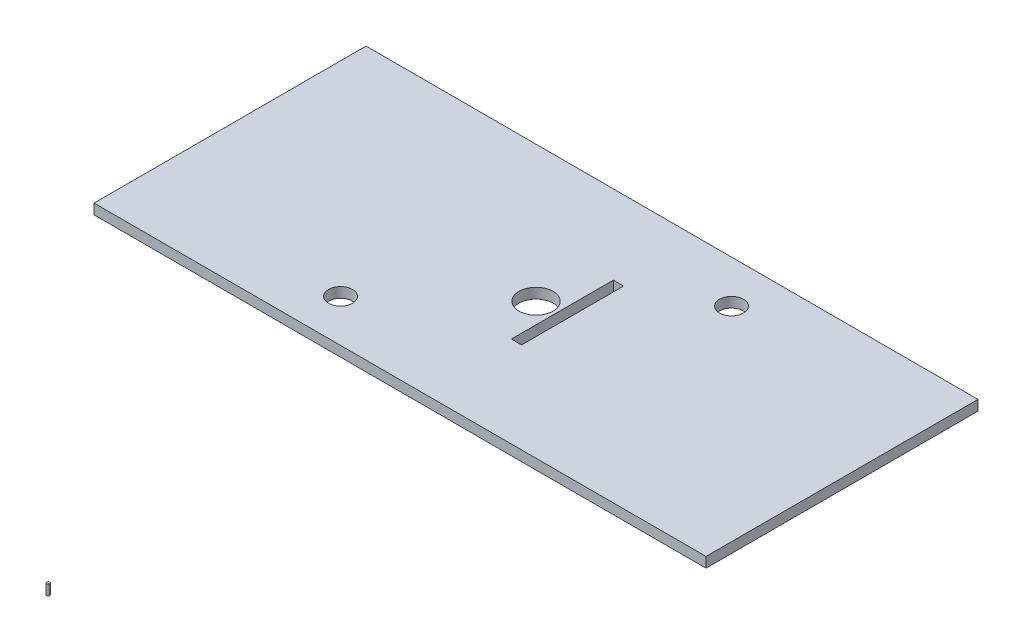
SolidWorks part; units mm, degrees
ref_plane "Plano frontal" through (0, 0, 0) normal (0, 0, 1) x (1, 0, 0)
ref_plane "Plano superior" through (0, 0, 0) normal (0, 1, 0) x (1, 0, 0)
ref_plane "Plano direito" through (0, 0, 0) normal (1, 0, 0) x (0, 0, -1)
sketch "Esboço1" plane through (0, 0, 0) normal (0, 1, 0) x (1, 0, 0)
  line L1 (90, -40) -> (-90, -40)
  line L2 (90, -40) -> (90, 40)
  line L3 (90, 40) -> (-90, 40)
  line L4 (-90, -40) -> (-90, 40)
  line L5 (90, -40) -> (-90, 40) construction
  line L6 (90, 40) -> (-90, -40) construction
  circle A0 centre (0, -143.5) radius 0.45
  circle A1 centre (0, 0) radius 5.025
  point P0 (0, 0)
  point P6 (0, 0)
  dimension "D3" = 10.05
  dimension "D1" = 80
  dimension "D2" = 180
extrude "Ressalto-extrusão1" add sketch "Esboço1" along normal blind 3
sketch "Esboço3" plane through (0, 3, 0) normal (0, 1, 0) x (1, 0, 0)
  circle A0 centre (30, 27.5) radius 3.525
  circle A1 centre (-30, -27.5) radius 3.525
  dimension "D1" = 7.05
  dimension "D2" = 7.05
  dimension "D3" = 30
  dimension "D4" = 30
  dimension "D5" = 27.5
  dimension "D6" = 27.5
extrude "Corte-extrusão2" cut sketch "Esboço3" against normal blind 100
sketch "Esboço4" plane through (0, 3, 0) normal (0, 1, 0) x (1, 0, 0)
  line L0 (-90, -40) -> (90, -40) construction
  line L1 (6, 16.7481) -> (9, 16.7481)
  line L2 (6, 16.7481) -> (6, -13.2519)
  line L3 (6, -13.2519) -> (9, -13.2519)
  line L4 (9, 16.7481) -> (9, -13.2519)
  line L5 (6, 16.7481) -> (9, -13.2519) construction
  line L6 (6, -13.2519) -> (9, 16.7481) construction
  point P0 (7.5, 1.7481)
  point P5 (0, 0)
  dimension "D1" = 3
  dimension "D2" = 30
  dimension "D3" = 7.5
  dimension "D4" = 41.7481
extrude "Corte-extrusão3" cut sketch "Esboço4" against normal blind 10
